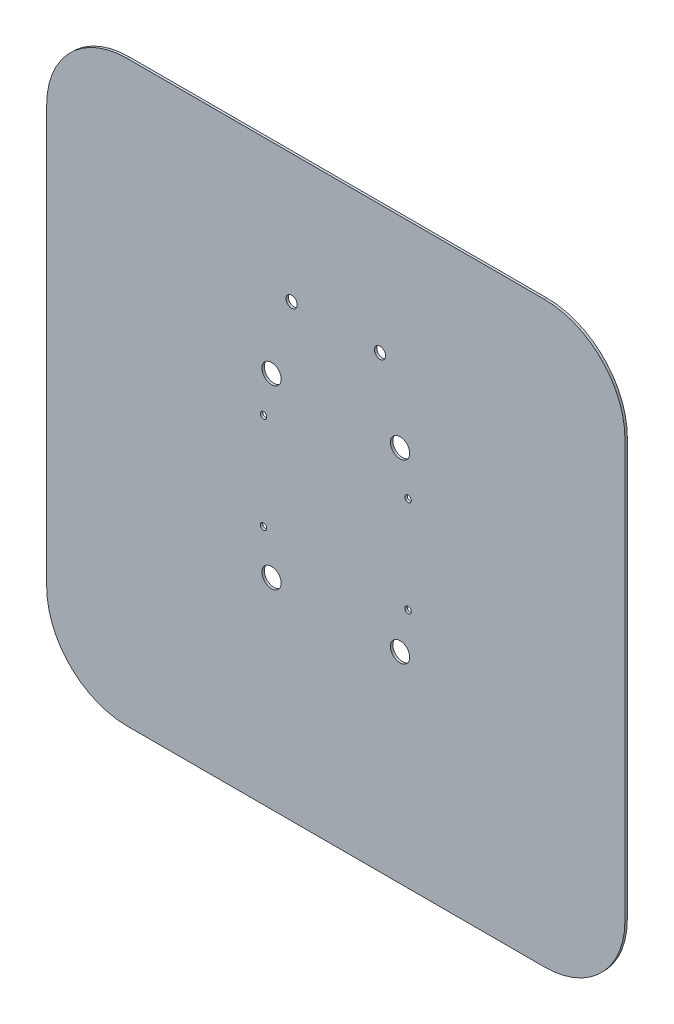
SolidWorks part; units mm, degrees
ref_plane "Front Plane" through (0, 0, 0) normal (0, 0, 1) x (1, 0, 0)
ref_plane "Top Plane" through (0, 0, 0) normal (0, 1, 0) x (1, 0, 0)
ref_plane "Right Plane" through (0, 0, 0) normal (1, 0, 0) x (0, 0, -1)
sketch "Sketch1" plane through (0, 0, 0) normal (0, 0, 1) x (1, 0, 0)
  line L1 (50, 0) -> (310, 0)
  line L2 (0, 50) -> (0, 310)
  line L3 (50, 360) -> (310, 360)
  line L4 (360, 50) -> (360, 310)
  arc A0 (0, 50) -> (50, 0) centre (50, 50) ccw
  arc A1 (360, 50) -> (310, 0) centre (310, 50) cw
  arc A2 (360, 310) -> (310, 360) centre (310, 310) ccw
  arc A3 (0, 310) -> (50, 360) centre (50, 310) cw
  point P7 (0, 0)
  point P13 (360, 360)
  point P16 (0, 360)
  dimension "D3" = 50
  dimension "D1" = 360
  dimension "D2" = 360
extrude "Boss-Extrude1" add sketch "Sketch1" along normal blind 1.5 contours L2 A3 L3 A2 L4 A1 L1 A0
sketch "Sketch2" plane through (0, 0, 1.5) normal (0, 0, 1) x (1, 0, 0)
  line L0 (0, 50) -> (0, 310) construction
  line L1 (50, 0) -> (310, 0) construction
  point P0 (180, 180)
  dimension "D1" = 180
  dimension "D2" = 180
hole_wizard "Ø4.0 (4) Diameter Hole1" positions "3DSketch1" profile "Sketch3" hole size "Ø4.0" standard "ISO" end condition through all
sketch3d "3DSketch1"
  line L0 (50, 0, 1.5) -> (310, 0, 1.5) construction
  line L1 (0, 50, 1.5) -> (0, 310, 1.5) construction
  point P0 (135, 210, 1.5)
  point P2 (225, 210, 1.5)
  point P4 (225, 150, 1.5)
  point P6 (135, 150, 1.5)
  dimension "D1" = 150
  dimension "D2" = 210
  dimension "D3" = 135
  dimension "D4" = 225
sketch "Sketch3" plane through (135, 210, 1.5) normal (1, 0, 0) x (0, -1, 0)
  line L0 (0, 0) -> (0, 1.5)
  line L1 (0, 1.5) -> (2, 1.5)
  line L2 (2, 1.5) -> (2, 0)
  line L5 (2, 0) -> (0, 0)
  line L11 (0, -6.35) -> (0, 107.95) construction
  dimension "Thru Hole Dia." = 4
  dimension "Thru Hole Depth" = 1.5
hole_wizard "Ø7.0 (7) Diameter Hole1" positions "3DSketch2" profile "Sketch4" hole size "Ø7.0" standard "ISO" end condition through all
sketch3d "3DSketch2"
  line L0 (50, 360, 1.5) -> (310, 360, 1.5) construction
  line L1 (0, 50, 1.5) -> (0, 310, 1.5) construction
  point P0 (152.5, 280, 1.5)
  point P2 (207.5, 280, 1.5)
  dimension "D1" = 80
  dimension "D2" = 152.5
  dimension "D3" = 55
sketch "Sketch4" plane through (152.5, 280, 1.5) normal (1, 0, 0) x (0, -1, 0)
  line L0 (0, 0) -> (0, 1.5)
  line L1 (0, 1.5) -> (3.5, 1.5)
  line L2 (3.5, 1.5) -> (3.5, 0)
  line L5 (3.5, 0) -> (0, 0)
  line L11 (0, -6.35) -> (0, 107.95) construction
  dimension "Thru Hole Dia." = 7
  dimension "Thru Hole Depth" = 1.5
hole_wizard "Ø12.0mm Dowel Hole1" positions "3DSketch3" profile "Sketch5" hole size "Ø12.0" standard "ISO" end condition through all
sketch3d "3DSketch3"
  line L0 (0, 50, 1.5) -> (0, 310, 1.5) construction
  line L1 (50, 0, 1.5) -> (310, 0, 1.5) construction
  point P0 (140, 235, 1.5)
  point P2 (220, 235, 1.5)
  point P4 (140, 125, 1.5)
  point P6 (220, 125, 1.5)
  dimension "D1" = 80
  dimension "D2" = 110
  dimension "D3" = 140
  dimension "D4" = 125
sketch "Sketch5" plane through (140, 235, 1.5) normal (1, 0, 0) x (0, -1, 0)
  line L0 (0, 0) -> (0, 1.5)
  line L1 (0, 1.5) -> (6, 1.5)
  line L2 (6, 1.5) -> (6, 0)
  line L5 (6, 0) -> (0, 0)
  line L11 (0, -6.35) -> (0, 107.95) construction
  dimension "Thru Hole Dia." = 12
  dimension "Thru Hole Depth" = 1.5
